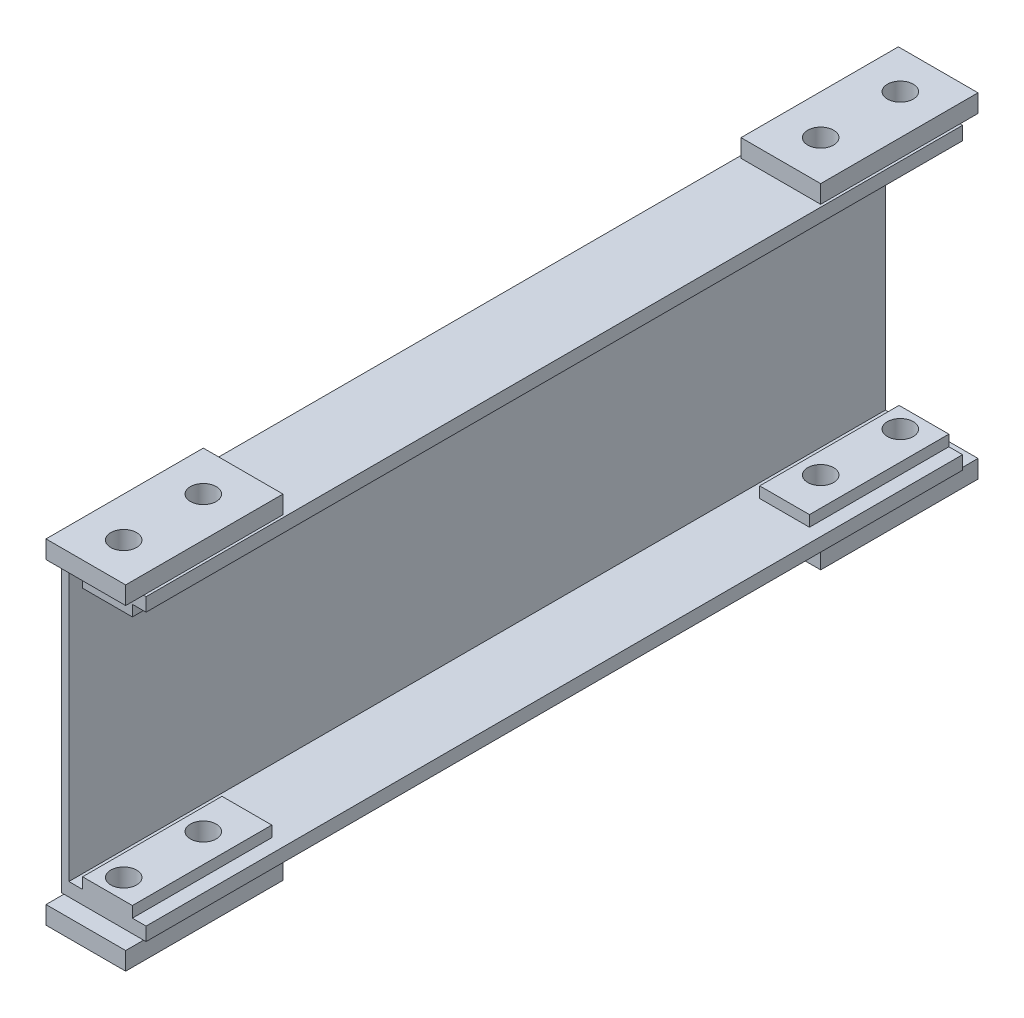
SolidWorks part; units mm, degrees
ref_plane "前视基准面" through (0, 0, 0) normal (0, 0, 1) x (1, 0, 0)
ref_plane "上视基准面" through (0, 0, 0) normal (0, 1, 0) x (1, 0, 0)
ref_plane "右视基准面" through (0, 0, 0) normal (1, 0, 0) x (0, 0, -1)
sketch "草图1" plane through (0, 0, 0) normal (0, 0, 1) x (1, 0, 0)
  line L1 (0, 0) -> (85, 0)
  line L2 (0, 0) -> (0, 300)
  line L3 (0, 300) -> (85, 300)
  line L4 (85, 0) -> (85, 300)
  dimension "D1" = 300
  dimension "D2" = 85
extrude "凸台-拉伸1" add sketch "草图1" along normal blind 820
sketch "草图2" plane through (0, 0, 820) normal (0, 0, 1) x (1, 0, 0)
  line L0 (85, 0) -> (85, 300) construction
  line L1 (7.5, 286.5) -> (85, 286.5)
  line L2 (7.5, 286.5) -> (7.5, 13.5)
  line L3 (7.5, 13.5) -> (85, 13.5)
  line L4 (85, 286.5) -> (85, 13.5)
  line L5 (85, 300) -> (0, 300) construction
  line L6 (0, 300) -> (0, 0) construction
  line L7 (0, 0) -> (85, 0) construction
  dimension "D1" = 13.5
  dimension "D2" = 7.5
  dimension "D3" = 13.5
extrude "切除-拉伸1" cut sketch "草图2" against normal through all
ref_plane "基准面1" through (0, 0, 410) normal (0, 0, -1) x (-1, 0, 0)
ref_plane "基准面2" through (0, 150, 0) normal (0, -1, 0) x (-1, 0, 0)
sketch "草图5" plane through (0, 286.5, 0) normal (0, -1, 0) x (1, 0, 0)
  line L0 (46.25, -1000) -> (46.25, 49000) construction
  line L1 (85, 0) -> (7.5, 0) construction
  line L3 (21.25, 0) -> (71.25, 0)
  line L4 (21.25, 0) -> (21.25, 140)
  line L5 (21.25, 140) -> (71.25, 140)
  line L6 (71.25, 0) -> (71.25, 140)
  point P5 (46.25, 0)
  dimension "D1" = 140
  dimension "D2" = 25
  dimension "D3" = 25
extrude "凸台-拉伸3" add sketch "草图5" along normal blind 11
sketch "草图6" plane through (0, 300, 0) normal (0, 1, 0) x (1, 0, 0)
  line L0 (42.5, -1000) -> (42.5, 49000) construction
  line L1 (85, 0) -> (0, 0) construction
  line L3 (82.5, 18) -> (2.5, 18)
  line L4 (82.5, 18) -> (82.5, -140)
  line L5 (82.5, -140) -> (2.5, -140)
  line L6 (2.5, 18) -> (2.5, -140)
  point P5 (42.5, 0)
  dimension "D1" = 80
  dimension "D2" = 158
  dimension "D3" = 140
extrude "凸台-拉伸4" add sketch "草图6" along normal blind 18
sketch "草图8" plane through (0, 318, 0) normal (0, 1, 0) x (1, 0, 0)
  line L0 (42.5, -982) -> (42.5, 49018) construction
  line L1 (82.5, 18) -> (2.5, 18) construction
  line L2 (2.5, -140) -> (82.5, -140) construction
  circle A0 centre (42.5, -20) radius 13
  circle A1 centre (42.5, -100) radius 13
  point P5 (42.5, 18)
  dimension "D1" = 26
  dimension "D2" = 80
  dimension "D3" = 40
extrude "切除-拉伸3" cut sketch "草图8" against normal through all
mirror "镜向3" about plane through (0, 150, 0) normal (0, -1, 0) of "切除-拉伸3", "凸台-拉伸4", "凸台-拉伸3"
mirror "镜向4" about plane through (0, 0, 410) normal (0, 0, -1) of "镜向3", "切除-拉伸3", "凸台-拉伸4", "凸台-拉伸3"
